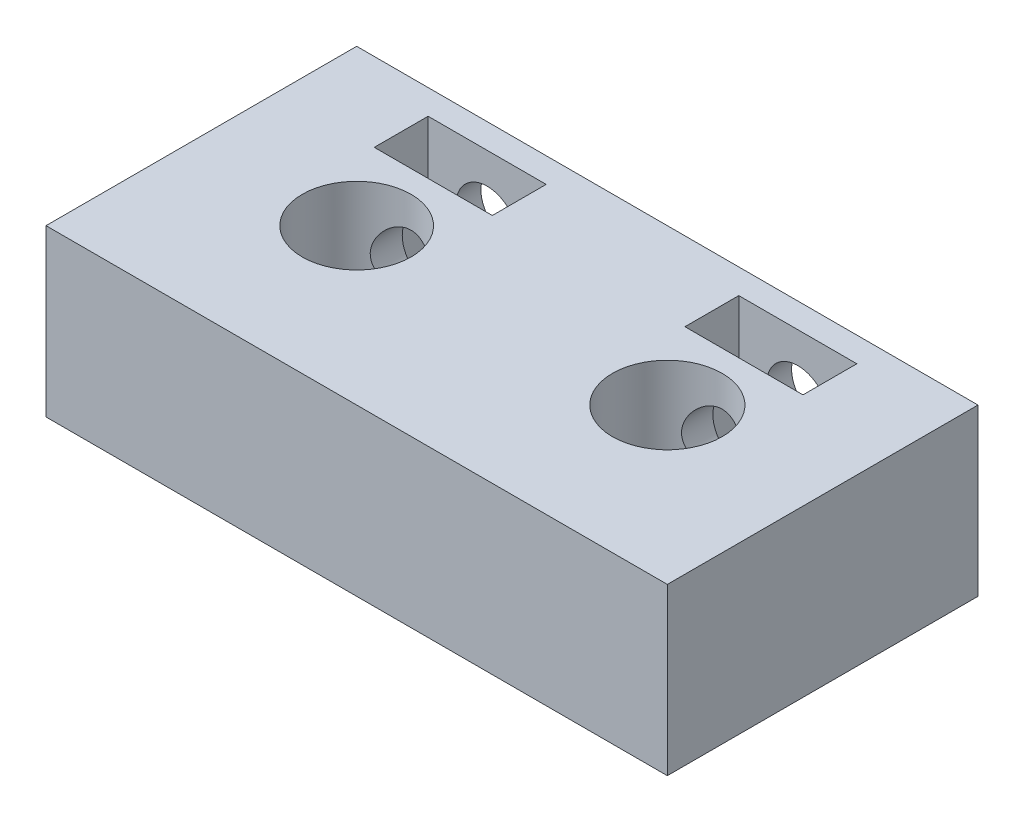
SolidWorks part; units mm, degrees
ref_plane "Front Plane" through (0, 0, 0) normal (0, 0, 1) x (1, 0, 0)
ref_plane "Top Plane" through (0, 0, 0) normal (0, 1, 0) x (1, 0, 0)
ref_plane "Right Plane" through (0, 0, 0) normal (1, 0, 0) x (0, 0, -1)
sketch "Sketch1" plane through (0, 0, 0) normal (0, 1, 0) x (1, 0, 0)
  line L0 (0, 7.5) -> (0, -7.5) construction
  line L1 (-15, -7.5) -> (15, -7.5)
  line L2 (-15, -7.5) -> (-15, 7.5)
  line L3 (-15, 7.5) -> (15, 7.5)
  line L4 (15, -7.5) -> (15, 7.5)
  line L5 (-15, -7.5) -> (15, 7.5) construction
  line L6 (-15, 7.5) -> (15, -7.5) construction
  line L7 (-10.35, 6.3) -> (-4.65, 6.3)
  line L8 (-10.35, 6.3) -> (-10.35, 3.7)
  line L9 (-10.35, 3.7) -> (-4.65, 3.7)
  line L10 (-4.65, 6.3) -> (-4.65, 3.7)
  line L11 (-10.35, 6.3) -> (-4.65, 3.7) construction
  line L12 (-10.35, 3.7) -> (-4.65, 6.3) construction
  line L13 (10.35, 3.7) -> (4.65, 3.7)
  line L14 (4.65, 6.3) -> (4.65, 3.7)
  line L15 (10.35, 6.3) -> (4.65, 6.3)
  line L16 (10.35, 6.3) -> (10.35, 3.7)
  circle A1 centre (-7.5, 0) radius 2.625
  circle A2 centre (7.5, 0) radius 2.65
  point P0 (0, 0)
  point P8 (-7.5, 5)
  dimension "D2" = 5.25
  dimension "D8" = 5.3
  dimension "D1" = 30
  dimension "D3" = 15
  dimension "D4" = 7.5
  dimension "D5" = 5.7
  dimension "D6" = 2.6
  dimension "D7" = 5
  dimension "D9" = 7.5
extrude "Boss-Extrude1" add sketch "Sketch1" along normal blind 6
sketch "Sketch3" plane through (0, 0, -7.5) normal (0, 0, -1) x (-1, 0, 0)
  line L0 (0, 0) -> (0, 6) construction
  line L1 (-15, 6) -> (15, 6) construction
  circle A0 centre (7.5, 3) radius 1.5
  circle A1 centre (-7.5, 3) radius 1.5
  point P8 (0, 3)
  dimension "D1" = 3
  dimension "D2" = 15
extrude "Cut-Extrude1" cut sketch "Sketch3" against normal blind 8
sketch "Sketch4" plane through (0, 0, 0) normal (0, -1, 0) x (1, 0, 0)
  line L1 (-15, 7.5) -> (15, 7.5)
  line L2 (-15, 7.5) -> (-15, -7.5)
  line L3 (-15, -7.5) -> (15, -7.5)
  line L4 (15, 7.5) -> (15, -7.5)
  circle A0 centre (-7.5, 0) radius 2.625
  circle A1 centre (-7.5, 0) radius 2.625 construction
  circle A2 centre (7.5, 0) radius 2.65
  circle A3 centre (7.5, 0) radius 2.65 construction
extrude "Boss-Extrude2" add sketch "Sketch4" along normal blind 2
